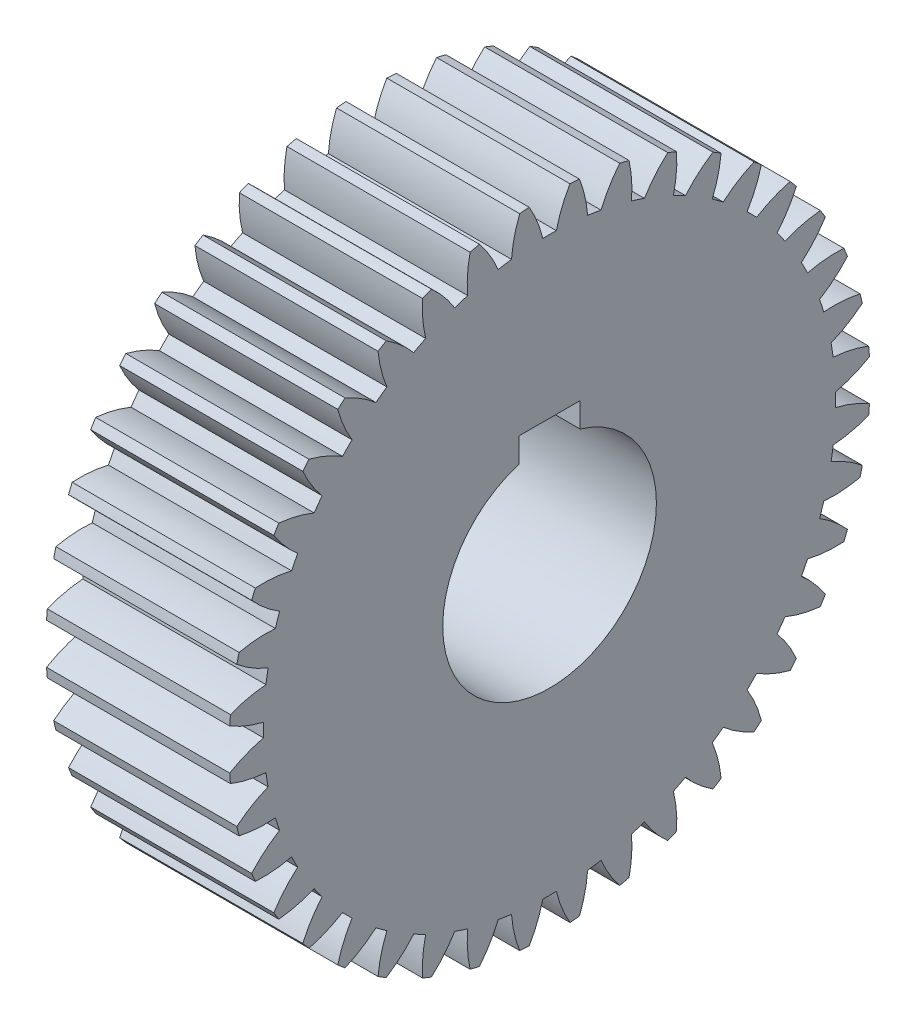
SolidWorks part; units mm, degrees
ref_plane "Plane1" through (0, 0, 0) normal (0, 0, 1) x (1, 0, 0)
ref_plane "Plane2" through (0, 0, 0) normal (0, 1, 0) x (1, 0, 0)
ref_plane "Plane3" through (0, 0, 0) normal (1, 0, 0) x (0, 0, -1)
sketch "HoldingSke" plane through (0, 0, 0) normal (0, 1, 0) x (1, 0, 0)
  line L0 (0, 0) -> (0.3064, -0.2571)
  line L1 (-15, 0) -> (100, 0) construction
  line L2 (0, 0) -> (-2.1039, 2.3779)
  line L3 (0, 0) -> (-11.863, 4.5341)
  line L4 (0, 0) -> (6.6156, 5.5511)
  line L5 (0, 0) -> (-46.8476, -17.4728)
  line L6 (0, 0) -> (-24.8689, -16.7791)
  line L7 (-2.1039, 2.3779) -> (8.6586, 51.2059)
  line L8 (-76.2, 54.61) -> (-72.9, 54.61)
  line L9 (-71.009, 38.7566) -> (-53.1078, 45.2721)
  line L10 (-76.2, 71.12) -> (104.1128, 71.12)
  line L11 (0, 0) -> (-30, 0)
  line L12 (-76.2, 101.6) -> (-76.113, 101.6)
  line L13 (24.9733, 27.94) -> (52.9518, 28.4284)
  line L14 (24.9733, 27.94) -> (24.9743, 27.94)
  line L15 (24.9733, 27.94) -> (100.4006, 29.5858)
  line L16 (-63.627, -2.5) -> (-12.827, -2.5)
  circle A0 centre (0, 0) radius 17.5
  circle A1 centre (0, 0) radius 37.5
  circle A2 centre (0, 0) radius 37.5
  circle A3 centre (0, 0) radius 17.5
  dimension "MHD" = 75
  dimension "Hub_dia" = 75
  dimension "Pitch" = 0.4
  dimension "Overall_len" = 50
  dimension "Thickness" = 30
  dimension "OAL" = 50.0001
  dimension "T_dim" = 3.3
  dimension "Ap" = 20
  dimension "H" = 19.05
  dimension "Pitch_radius" = 180.3128
  dimension "Width" = 30
  dimension "Backlash" = 0.087
  dimension "Addendum_fac" = 1
  dimension "Dedendum_fac" = 1.25
  dimension "Clearance_fac" = 0.25
  dimension "Dedendum_add" = 0.001
  dimension "Module" = 2.5
sketch "BasProSke" plane through (0, 0, 0) normal (0, 1, 0) x (1, 0, 0)
  line L0 (-10, 0) -> (60, 0) construction
  line L1 (0, 0) -> (0, 52.5)
  line L2 (0, 0) -> (30, 0)
  line L3 (30, 0) -> (30, 52.5)
  line L4 (30, 52.5) -> (0, 52.5)
  dimension "Thickness" = 30
revolve "Base-Revolve" add sketch "BasProSke" angle 360 about L0
sketch "TooCutSke" plane through (0, 0, 0) normal (1, 0, 0) x (0, 0, -1)
  line L1 (0, 0) -> (0, 107) construction
  line L2 (0, 0) -> (-2.1152, 49.9552) construction
  line L3 (0, 0) -> (-7.8408, 99.6263) construction
  line L4 (-2.1152, 49.9552) -> (-3.9204, 49.8132) construction
  arc A0 (1.1089, 46.8609) -> (-1.1089, 46.8609) centre (0, 0) ccw
  arc A1 (3.3504, 52.4184) -> (-3.3504, 52.4184) centre (0, 0) ccw
  circle A2 centre (0, 0) radius 50 construction
  circle A3 centre (0, 0) radius 46.9846 construction
  arc A4 (-1.1089, 46.8609) -> (-3.3504, 52.4184) centre (-20.5685, 42.2432) ccw
  arc A5 (3.3504, 52.4184) -> (1.1089, 46.8609) centre (20.5685, 42.2432) ccw
  dimension "Half_CT" = 1.8107
extrude "ToothCut" cut sketch "TooCutSke" along normal through all
fillet "Breaks" [suppressed] radius 0.05
fillet "RootFillets" [suppressed] radius 0.626
pattern_circular "TeethCuts" count 40 every 9 about axis through (-10, 0, 0) along (1, 0, 0) of "ToothCut", "RootFillets", "Breaks"
sketch "HubNeaOneSke" plane through (0, 0, 0) normal (-1, 0, 0) x (0, 0, 1)
  circle A0 centre (0, 0) radius 37.5
  dimension "Diameter" = 75
extrude "HubNearOne" [suppressed] add sketch "HubNeaOneSke" along normal blind 20.0001
sketch "HubNeaBotSke" plane through (0, 0, 0) normal (-1, 0, 0) x (0, 0, 1)
  circle A0 centre (0, 0) radius 37.5
  dimension "Diameter" = 75
extrude "HubNearBoth" [suppressed] add sketch "HubNeaBotSke" along normal blind 10
ref_plane "FarPln" through (30, 0, 0) normal (1, 0, 0) x (0, 0, -1)
sketch "HubFarSke" plane through (30, 0, 0) normal (1, 0, 0) x (0, 0, -1)
  circle A0 centre (0, 0) radius 37.5
  dimension "Diameter" = 75
extrude "HubFar" [suppressed] add sketch "HubFarSke" along normal blind 10
sketch "BorSke" plane through (0, 0, 0) normal (1, 0, 0) x (0, 0, -1)
  circle A0 centre (0, 0) radius 17.5
extrude "Bore" cut sketch "BorSke" along normal mid plane 100.0001
sketch "KeySke" plane through (0, 0, 0) normal (1, 0, 0) x (0, 0, -1)
  line L0 (-5, 0) -> (-5, 20.8)
  line L1 (-5, 20.8) -> (5, 20.8)
  line L2 (5, 20.8) -> (5, 0)
  line L3 (0, 0) -> (0, 34) construction
  line L4 (-5, 0) -> (5, 0)
extrude "Keyway" cut sketch "KeySke" along normal mid plane 100.0001
pattern_circular "Keyway2" [suppressed] count 2 every 90 about axis through (-10, 0, 0) along (1, 0, 0)
equation "' \"Module@HoldingSke\" = 6.35"
equation "' \"Num_teeth@HoldingSke\" = 12"
equation "' \"Ap@HoldingSke\" =  20"
equation "' \"Ap@HoldingSke\" = 20"
equation "' \"Width@HoldingSke\" = 0.5 * 25.4"
equation "' \"Hub_dia@HoldingSke\"= 1 * 25.4"
equation "' \"Hub_dia@HoldingSke\" = 1 * 25.4"
equation "' \"Overall_len@HoldingSke\" = 1.0 * 25.4"
equation "' \"Bore@HoldingSke\" = 0.75 * 25.4"
equation "' \"T_dim@HoldingSke\" = 0.1 * 25.4"
equation "' \"Width@KeySke\" = 0.25 * 25.4"
equation "' \"Show_teeth@HoldingSke\" = 13"
equation "' \"Backlash@HoldingSke\" = 0.009 * 25.4"
equation "' \"Addendum_fac@HoldingSke\" = 1.0"
equation "' \"Dedendum_fac@HoldingSke\" = 1.25"
equation "' \"Dedendum_add@HoldingSke\" = 0.00005 * 25.4"
equation "' \"Clearance_fac@HoldingSke\" = 0.25"
equation "\"Pitch@HoldingSke\" = 1 / \"Module@HoldingSke\""
equation "\"Overcut_dia@TooCutSke\" = (\"Num_teeth@HoldingSke\" + 2 * \"Addendum_fac@HoldingSke\") / \"Pitch@HoldingSke\" + 0.002 * 25.4"
equation "\"Pitch_dia@TooCutSke\" = \"Num_teeth@HoldingSke\" / \"Pitch@HoldingSke\""
equation "\"Base_dia@TooCutSke\" = \"Num_teeth@HoldingSke\" / \"Pitch@HoldingSke\" * cos((\"Ap@HoldingSke\"  * 3.14159265 / 180))"
equation "\"Root_dia@TooCutSke\" = (\"Num_teeth@HoldingSke\" + 2) / \"Pitch@HoldingSke\" - 2 * (\"Addendum_fac@HoldingSke\" + \"Dedendum_fac@HoldingSke\") / \"Pitch@HoldingSke\" - \"Dedendum_add@HoldingSke\" * 2"
equation "\"Half_ang@TooCutSke\" = 180 / \"Num_teeth@HoldingSke\""
equation "\"Half_CT@TooCutSke\" = \"Num_teeth@HoldingSke\" / \"Pitch@HoldingSke\" * sin((3.14159265 / 2 / \"Num_teeth@HoldingSke\")) / 2 - 7 * \"Backlash@HoldingSke\" / 4"
equation "\"Flank_rad@TooCutSke\" = \"Num_teeth@HoldingSke\" / \"Pitch@HoldingSke\" / 5"
equation "\"Radius@RootFillets\" = \"Clearance_fac@HoldingSke\" / \"Pitch@HoldingSke\" + \"Dedendum_add@HoldingSke\""
equation "\"Break_rad@Breaks\" = 0.02 / \"Pitch@HoldingSke\""
equation "\"Thickness@HoldingSke\" = \"Width@HoldingSke\""
equation "\"OAL@HoldingSke\" = \"Thickness@HoldingSke\""
equation "\"MHD@HoldingSke\" = (\"Num_teeth@HoldingSke\" + 2) / \"Pitch@HoldingSke\" - 2 * (\"Addendum_fac@HoldingSke\" + \"Dedendum_fac@HoldingSke\")  / \"Pitch@HoldingSke\" - \"Dedendum_add@HoldingSke\" * 2"
equation "\"MBD@HoldingSke\" = (\"Num_teeth@HoldingSke\" + 2) / \"Pitch@HoldingSke\" - 2 * (\"Addendum_fac@HoldingSke\" + \"Dedendum_fac@HoldingSke\")  / \"Pitch@HoldingSke\" - \"Dedendum_add@HoldingSke\" * 2 - 0.002 * 25.4"
equation "\"MHD@HoldingSke\" = ((sgn( \"MHD@HoldingSke\" - \"Hub_dia@HoldingSke\" )-1)*( \"MHD@HoldingSke\" - \"Hub_dia@HoldingSke\" ))/-2+ \"Hub_dia@HoldingSke\""
equation "\"MBD@HoldingSke\" = ((sgn( \"MBD@HoldingSke\" - \"Bore@HoldingSke\" )-1)*( \"MBD@HoldingSke\" - \"Bore@HoldingSke\" ))/-2+ \"Bore@HoldingSke\""
equation "\"OAL@HoldingSke\" = ((sgn( \"OAL@HoldingSke\" - \"Overall_len@HoldingSke\" )+1)*( \"OAL@HoldingSke\" - \"Overall_len@HoldingSke\" ))/2 + \"Overall_len@HoldingSke\" + 0.000002 * 25.4"
equation "\"Num_teeth@TeethCuts\" = int( \"Show_teeth@HoldingSke\" ) + 1"
equation "\"Num_teeth@TeethCuts\" = ((sgn( \"Num_teeth@TeethCuts\" - \"Num_teeth@HoldingSke\" )-1)*( \"Num_teeth@TeethCuts\" - \"Num_teeth@HoldingSke\" ))/-2+ \"Num_teeth@HoldingSke\""
equation "\"Num_teeth@TeethCuts\" = ((sgn( \"Num_teeth@TeethCuts\" - 2.0)+1)*( \"Num_teeth@TeethCuts\" - 2.0))/2 +2.0"
equation "\"Angle@TeethCuts\" = 360.0 / \"Num_teeth@HoldingSke\""
equation "\"Diameter@BasProSke\" = (\"Num_teeth@HoldingSke\" + 2 * \"Addendum_fac@HoldingSke\") / \"Pitch@HoldingSke\""
equation "\"Thickness@BasProSke\"  = \"Thickness@HoldingSke\""
equation "' \"Fillet_rad@BasProSke\" =  \"Thickness@HoldingSke\" * 0.05"
equation "' \"Fillet_rad@BasProSke\" = \"Thickness@HoldingSke\" * 0.05"
equation "\"MHD@HoldingSke\" = ((sgn( \"MHD@HoldingSke\" - \"Root_dia@TooCutSke\" )-1)*( \"MHD@HoldingSke\" - \"Root_dia@TooCutSke\" ))/-2+ \"Root_dia@TooCutSke\""
equation "\"Diameter@HubNeaOneSke\" = \"MHD@HoldingSke\""
equation "\"Length@HubNearOne\" = \"OAL@HoldingSke\" - \"Thickness@BasProSke\""
equation "\"Diameter@HubNeaBotSke\" = \"MHD@HoldingSke\""
equation "\"Length@HubNearBoth\" = ( \"OAL@HoldingSke\" - \"Thickness@BasProSke\" ) / 2.0"
equation "\"Thickness@FarPln\" = \"Thickness@BasProSke\""
equation "\"Diameter@HubFarSke\" = \"MHD@HoldingSke\""
equation "\"Length@HubFar\" = ( \"OAL@HoldingSke\" - \"Thickness@BasProSke\" ) / 2.0"
equation "\"Diameter@BorSke\" = \"MBD@HoldingSke\""
equation "\"D1@Bore\" = \"OAL@HoldingSke\" * 2.0"
equation "\"D1@Keyway\" = \"OAL@HoldingSke\" * 2.0"
equation "\"Offset@KeySke\" = \"T_dim@HoldingSke\" + \"MBD@HoldingSke\" / 2.0"
